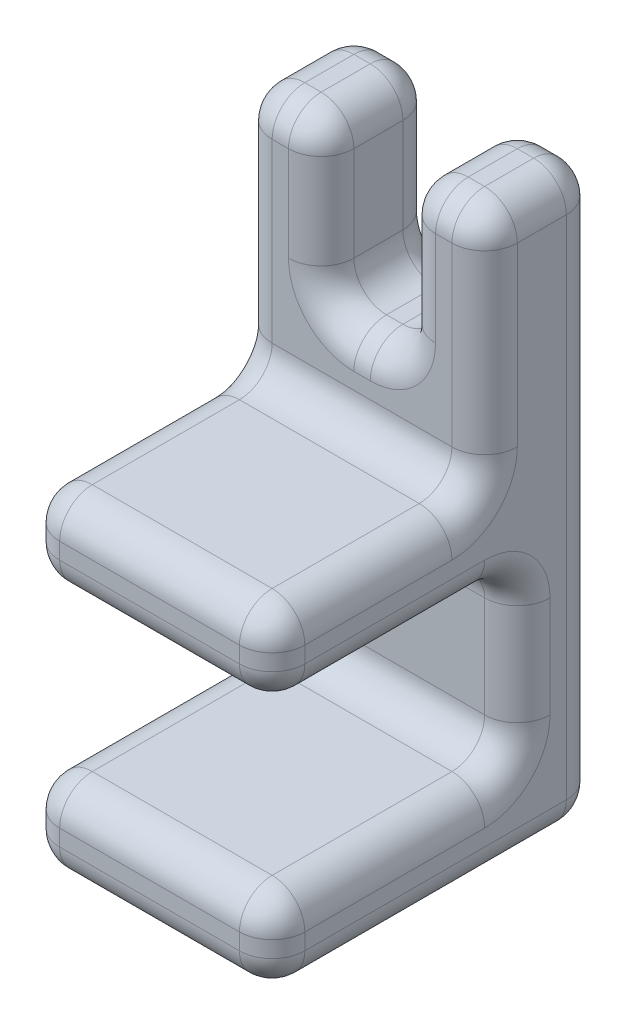
SolidWorks part; units mm, degrees
ref_plane "Front Plane" through (0, 0, 0) normal (0, 0, 1) x (1, 0, 0)
ref_plane "Top Plane" through (0, 0, 0) normal (0, 1, 0) x (1, 0, 0)
ref_plane "Right Plane" through (0, 0, 0) normal (1, 0, 0) x (0, 0, -1)
sketch "Sketch1" plane through (0, 0, 0) normal (0, 0, 1) x (1, 0, 0)
  line L1 (0, 0) -> (-15, 0)
  line L2 (0, 0) -> (0, 35)
  line L3 (0, 35) -> (-15, 35)
  line L4 (-15, 0) -> (-15, 35)
  dimension "D1" = 35
  dimension "D2" = 15
extrude "Boss-Extrude1" add sketch "Sketch1" along normal blind 20
sketch "Sketch2" plane through (0, 0, 0) normal (1, 0, 0) x (0, 0, -1)
  line L0 (-20, 0) -> (-20, 35) construction
  line L1 (-20, 15.2) -> (-5, 15.2)
  line L2 (-20, 15.2) -> (-20, 5)
  line L3 (-20, 5) -> (-5, 5)
  line L4 (-5, 15.2) -> (-5, 5)
  line L5 (-20, 0) -> (0, 0) construction
  line L6 (0, 0) -> (0, 35) construction
  dimension "10,5" = 10.2
  dimension "D1" = 5
  dimension "D2" = 5
extrude "Cut-Extrude1" cut sketch "Sketch2" against normal through all
fillet "Fillet1" radius 2 8 edges at (-15, 5, 12.5) (0, 5, 12.5) (-15, 15.2, 12.5) (0, 15.2, 12.5) (-7.5, 5, 5) (-15, 10.1, 5) (-7.5, 15.2, 5) (0, 10.1, 5)
sketch "Sketch4" plane through (-15, 0, 0) normal (-1, 0, 0) x (0, 0, 1)
  line L1 (20, 20.2) -> (7, 20.2)
  line L2 (20, 20.2) -> (20, 35)
  line L3 (20, 35) -> (7, 35)
  line L4 (7, 20.2) -> (7, 35)
  line L12 (20, 15.2) -> (7, 15.2) construction
  dimension "D1" = 5
extrude "Cut-Extrude3" cut sketch "Sketch4" against normal through all
sketch "Sketch5" plane through (0, 0, 0) normal (0, 0, -1) x (-1, 0, 0)
  line L1 (5, 35) -> (10, 35)
  line L2 (5, 35) -> (5, 25.2)
  line L3 (5, 25.2) -> (10, 25.2)
  line L4 (10, 35) -> (10, 25.2)
  line L6 (5, 25.2) -> (10, 25.2) construction
  line L9 (0, 35) -> (15, 35) construction
  line L10 (0, 35) -> (15, 35) construction
  line L11 (0, 20.2) -> (15, 20.2) construction
  point P10 (7.5, 35)
  point P11 (7.5, 35)
  dimension "D1" = 5
  dimension "D2" = 5
extrude "Cut-Extrude4" cut sketch "Sketch5" against normal up to next and the other way through all
fillet "Fillet2" radius 2 38 edges at (-10, 35, 3.5) (-5, 35, 3.5) (-5, 25.2, 3.5) (-10, 25.2, 3.5) (-2.5, 35, 7) (-12.5, 35, 7) (-10, 30.1, 7) (-7.5, 25.2, 7) (-5, 30.1, 7) (-7.5, 20.2, 7) (-15, 35, 3.5) (-15, 27.6, 7) (-15, 20.2, 13.5) (-0.5858, 4.4142, 20) (-15, 1.5, 20) (-14.4142, 4.4142, 20) (-7.5, 5, 20) (-0.5858, 15.7858, 20) (-7.5, 15.2, 20) (-14.4142, 15.7858, 20) (-15, 18.7, 20) (-7.5, 20.2, 20) (0, 35, 3.5) (0, 1.5, 20) (0, 18.7, 20) (0, 20.2, 13.5) (0, 27.6, 7) (-15, 0, 10) (-7.5, 0, 20) (0, 0, 10) (-7.5, 25.2, 0) (-10, 30.1, 0) (-12.5, 35, 0) (-15, 17.5, 0) (-7.5, 0, 0) (0, 17.5, 0) (-2.5, 35, 0) (-5, 30.1, 0)
equation "\"A\"= 10.2mm"
equation "\"10,5@Sketch2\" = \"A\""
